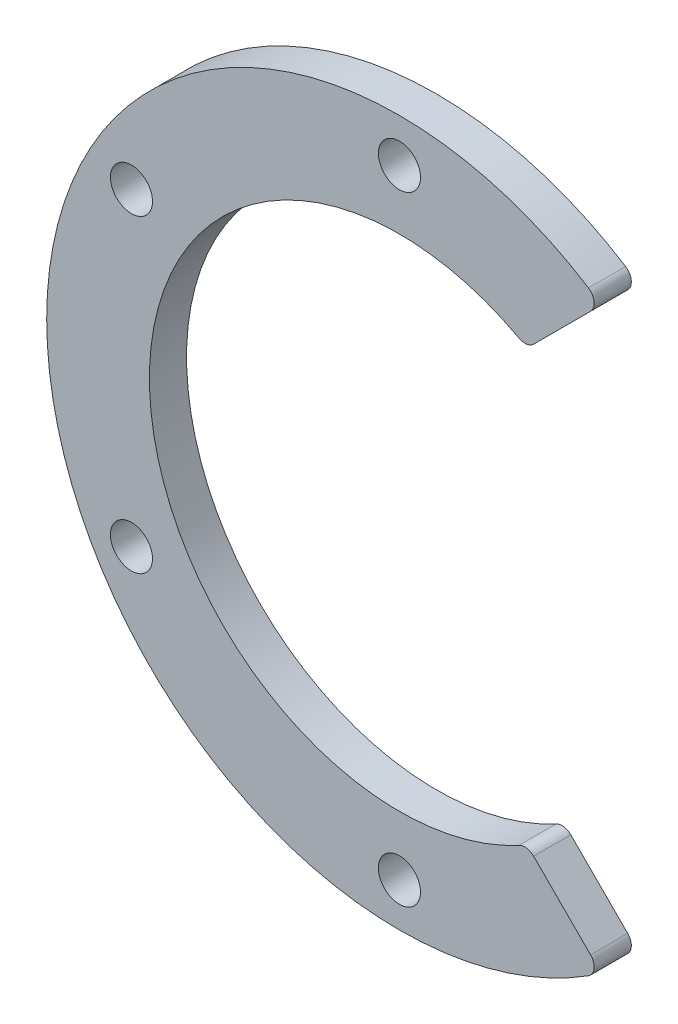
SolidWorks part; units mm, degrees
ref_plane "前视基准面" through (0, 0, 0) normal (0, 0, 1) x (1, 0, 0)
ref_plane "上视基准面" through (0, 0, 0) normal (0, 1, 0) x (1, 0, 0)
ref_plane "右视基准面" through (0, 0, 0) normal (1, 0, 0) x (0, 0, -1)
ref_plane "基准面1" through (0, 0, 0) normal (0, 0, -1) x (-1, 0, 0)
sketch "草图1" plane through (0, 0, 0) normal (0, 0, -1) x (-1, 0, 0)
  line L0 (-15.4414, 22.5125) -> (-10.8422, 17.9133)
  line L1 (-10.8422, -17.9133) -> (-15.4414, -22.5125)
  circle A0 centre (0, 25) radius 1.7
  circle A1 centre (0, -25) radius 1.7
  circle A2 centre (21.6506, 12.5) radius 1.7
  circle A3 centre (21.6506, -12.5) radius 1.7
  arc A4 (-15.2701, -24.0639) -> (-15.2701, 24.0639) centre (0, 0) ccw
  arc A5 (-15.2701, 24.0639) -> (-15.4414, 22.5125) centre (-14.7343, 23.2196) ccw
  arc A6 (-10.8422, 17.9133) -> (-9.657, 17.7421) centre (-10.1351, 18.6204) ccw
  arc A7 (-9.657, 17.7421) -> (-9.657, -17.7421) centre (0, 0) cw
  arc A8 (-9.657, -17.7421) -> (-10.8422, -17.9133) centre (-10.1351, -18.6204) ccw
  arc A9 (-15.4414, -22.5125) -> (-15.2701, -24.0639) centre (-14.7343, -23.2196) ccw
extrude "凸台-拉伸1" add sketch "草图1" against normal blind 3
